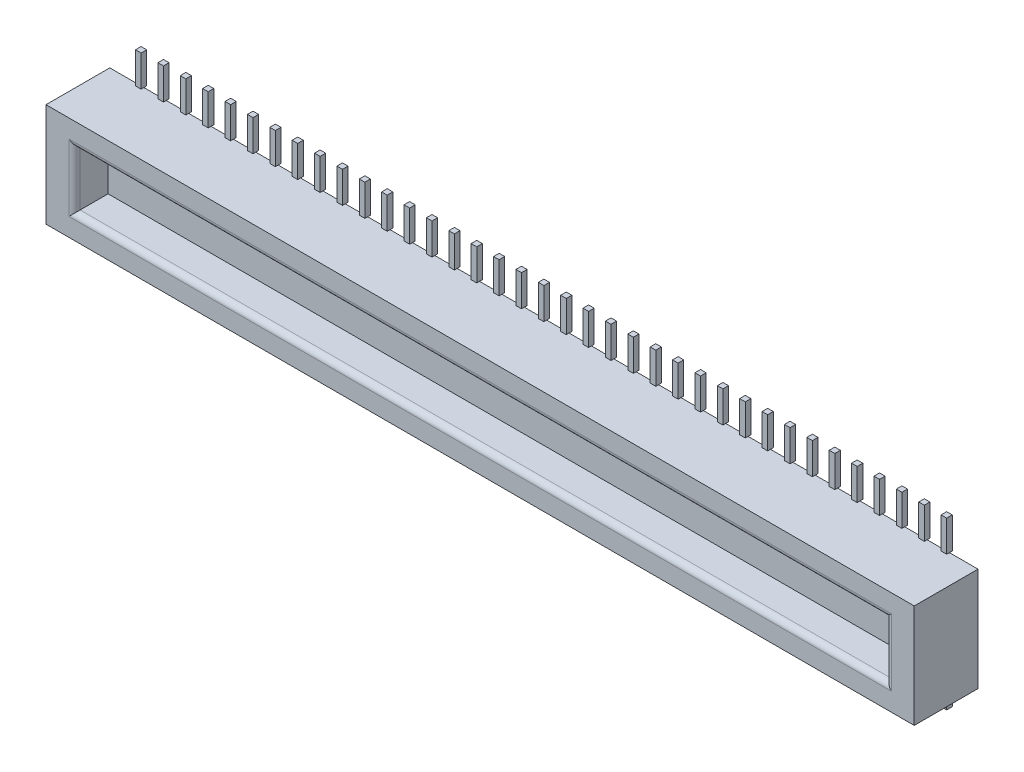
SolidWorks part; units mm, degrees
ref_plane "Front Plane" through (0, 0, 0) normal (0, 0, 1) x (1, 0, 0)
ref_plane "Top Plane" through (0, 0, 0) normal (0, 1, 0) x (1, 0, 0)
ref_plane "Right Plane" through (0, 0, 0) normal (1, 0, 0) x (0, 0, -1)
sketch "Sketch1" plane through (0, 0, 0) normal (0, 0, 1) x (1, 0, 0)
  line L1 (-7.76, -0.925) -> (7.76, -0.925)
  line L2 (-7.76, -0.925) -> (-7.76, 0.925)
  line L3 (-7.76, 0.925) -> (7.76, 0.925)
  line L4 (7.76, -0.925) -> (7.76, 0.925)
  line L5 (-7.76, -0.925) -> (7.76, 0.925) construction
  line L6 (-7.76, 0.925) -> (7.76, -0.925) construction
  point P0 (0, 0)
  dimension "D1" = 15.52
  dimension "D2" = 1.85
extrude "Boss-Extrude1" add sketch "Sketch1" along normal blind 1.14
sketch "Sketch2" plane through (0, 0, 1.14) normal (0, 0, 1) x (1, 0, 0)
  line L1 (-7.25, -0.5) -> (7.25, -0.5)
  line L2 (-7.25, -0.5) -> (-7.25, 0.5)
  line L3 (-7.25, 0.5) -> (7.25, 0.5)
  line L4 (7.25, -0.5) -> (7.25, 0.5)
  line L5 (-7.25, -0.5) -> (7.25, 0.5) construction
  line L6 (-7.25, 0.5) -> (7.25, -0.5) construction
  point P0 (0, 0)
  dimension "D1" = 14.5
  dimension "D2" = 1
extrude "Cut-Extrude1" cut sketch "Sketch2" against normal blind 0.6
sketch "Sketch3" plane through (0, -0.925, 0) normal (0, -1, 0) x (1, 0, 0)
  line L1 (-0.05, 0.05) -> (0.05, 0.05)
  line L2 (-0.05, 0.05) -> (-0.05, -0.05)
  line L3 (-0.05, -0.05) -> (0.05, -0.05)
  line L4 (0.05, 0.05) -> (0.05, -0.05)
  line L5 (-0.05, 0.05) -> (0.05, -0.05) construction
  line L6 (-0.05, -0.05) -> (0.05, 0.05) construction
  line L7 (-7.76, 0) -> (7.76, 0) construction
  point P0 (0, 0)
  point P5 (0.05, -0.0351)
  point P7 (0, 0)
  dimension "D1" = 0.1
  dimension "D2" = 0.05
  dimension "D3" = 0.1
extrude "Boss-Extrude2" add sketch "Sketch3" along normal blind 0.56
pattern_linear "LPattern1" count 19 spacing 0.4 along (-1, 0, 0) count 19 spacing 0.4 along (1, 0, 0) of "Boss-Extrude2"
mirror "Mirror1" about plane through (0, 0, 0) normal (0, 1, 0) of "LPattern1", "Boss-Extrude2"
fillet "Fillet1" radius 0.1 4 edges at (7.25, 0, 1.14) (0, -0.5, 1.14) (-7.25, 0, 1.14) (0, 0.5, 1.14)
